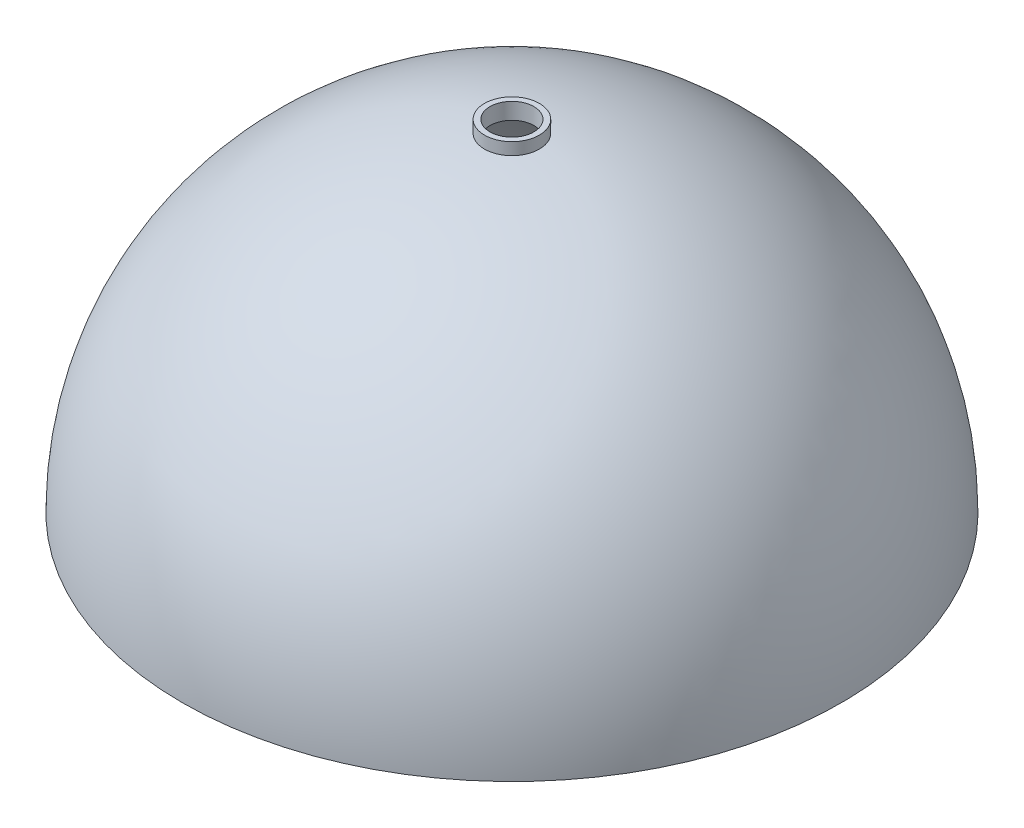
SolidWorks part; units mm, degrees
material "Plain Carbon Steel"
ref_plane "Front Plane" through (0, 0, 0) normal (0, 0, 1) x (1, 0, 0)
ref_plane "Top Plane" through (0, 0, 0) normal (0, 1, 0) x (1, 0, 0)
ref_plane "Right Plane" through (0, 0, 0) normal (1, 0, 0) x (0, 0, -1)
sketch "Sketch1" plane through (0, 0, 0) normal (0, 0, 1) x (1, 0, 0)
  line L0 (5, 0) -> (0, 0)
  line L1 (300, 300) -> (300, 295)
  arc A0 (0, 0) -> (300, 300) centre (300, 0) cw
  arc A1 (5, 0) -> (300, 295) centre (300, 0) cw
  dimension "D1" = 5
  dimension "D2" = 5
  dimension "D3" = 295
  dimension "D4" = 295
revolve "Revolve1" add sketch "Sketch1" angle 360 about L1
sketch "Sketch3" plane through (0, 0, 0) normal (0, 1, 0) x (1, 0, 0)
  circle A0 centre (300, 0) radius 25
  dimension "D1" = 50
extrude "Boss-Extrude1" add sketch "Sketch3" along normal blind 310
sketch "Sketch5" plane through (0, 0, 0) normal (0, 0, 1) x (1, 0, 0)
  line L3 (300.7553, 295.7553) -> (300.7553, 0)
  line L4 (300.7553, 0) -> (5, 0)
  arc A0 (5, 0) -> (300.7553, 295.7553) centre (300.7553, 0) cw
  point P0 (5, 0)
  point P11 (300.7553, 295.7427)
revolve "Cut-Revolve1" cut sketch "Sketch5" angle 360 about L3
sketch "Sketch6" plane through (0, 310, 0) normal (0, 1, 0) x (1, 0, 0)
  circle A0 centre (300, 0) radius 20
  dimension "D1" = 40
extrude "Cut-Extrude2" cut sketch "Sketch6" against normal blind 330
